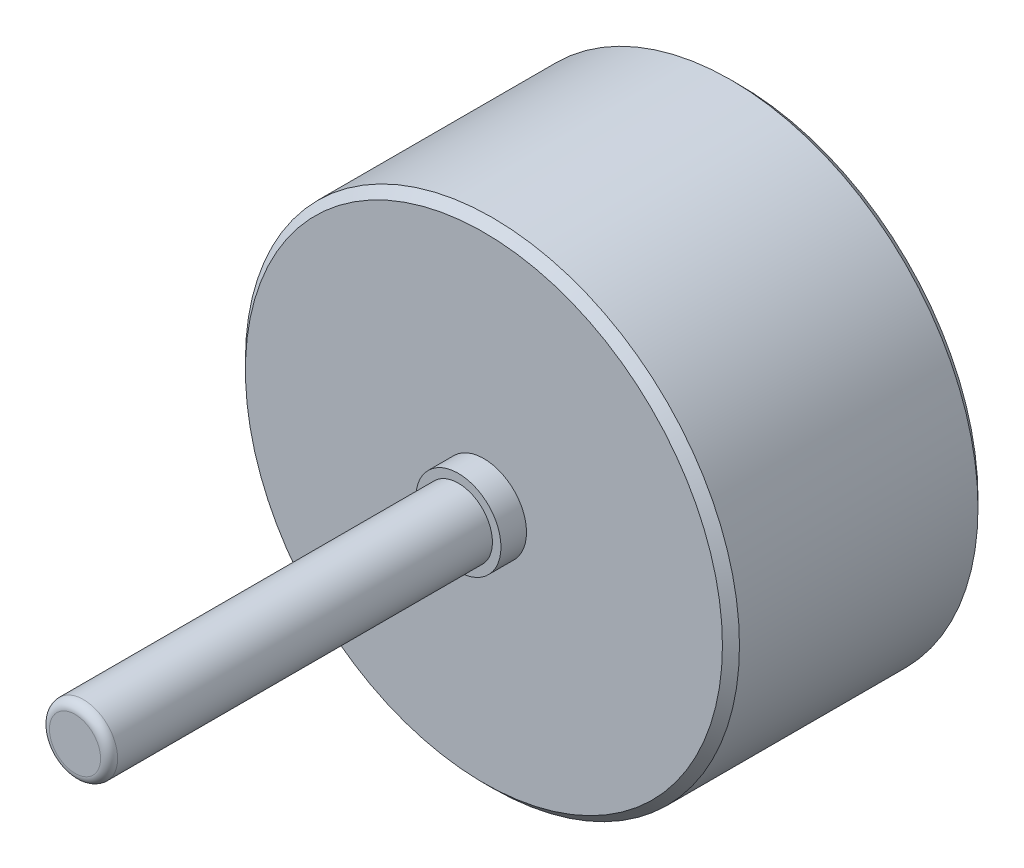
SolidWorks part; units mm, degrees
ref_plane "Plan de face" through (0, 0, 0) normal (0, 0, 1) x (1, 0, 0)
ref_plane "Plan de dessus" through (0, 0, 0) normal (0, 1, 0) x (1, 0, 0)
ref_plane "Plan de droite" through (0, 0, 0) normal (1, 0, 0) x (0, 0, -1)
sketch "Esquisse1" plane through (0, 0, 0) normal (0, 0, 1) x (1, 0, 0)
  circle A0 centre (0, 0) radius 29
extrude "Boss.-Extru.1" add sketch "Esquisse1" along normal blind 30
sketch "Esquisse2" plane through (0, 0, 30) normal (0, 0, 1) x (1, 0, 0)
  circle A0 centre (0, 0) radius 4
  dimension "D1" = 8
extrude "Boss.-Extru.2" add sketch "Esquisse2" along normal blind 10 contours A0
sketch "Esquisse3" plane through (0, 0, 30) normal (0, 0, 1) x (1, 0, 0)
  circle A0 centre (0, 0) radius 5
extrude "Boss.-Extru.3" add sketch "Esquisse3" along normal blind 3
sketch "Esquisse4" plane through (0, 0, 0) normal (0, 0, -1) x (-1, 0, 0)
  circle A0 centre (0, 0) radius 4
extrude "Enlèv. mat.-Extru.1" cut sketch "Esquisse4" against normal blind 5
chamfer "Chanfrein1" distance 1 angle 45 2 edges at (29, 0, 30) (29, 0, 0)
sketch "Esquisse5" plane through (0, 0, 40) normal (0, 0, 1) x (1, 0, 0)
  circle A0 centre (0, 0) radius 4
sketch "Esquisse8" plane through (0, 0, 40) normal (0, 0, 1) x (1, 0, 0)
  circle A0 centre (0, 0) radius 4
extrude "Boss.-Extru.4" add sketch "Esquisse8" along normal blind 38
fillet "Congé1" radius 1 1 edges at (4, 0, 78)
